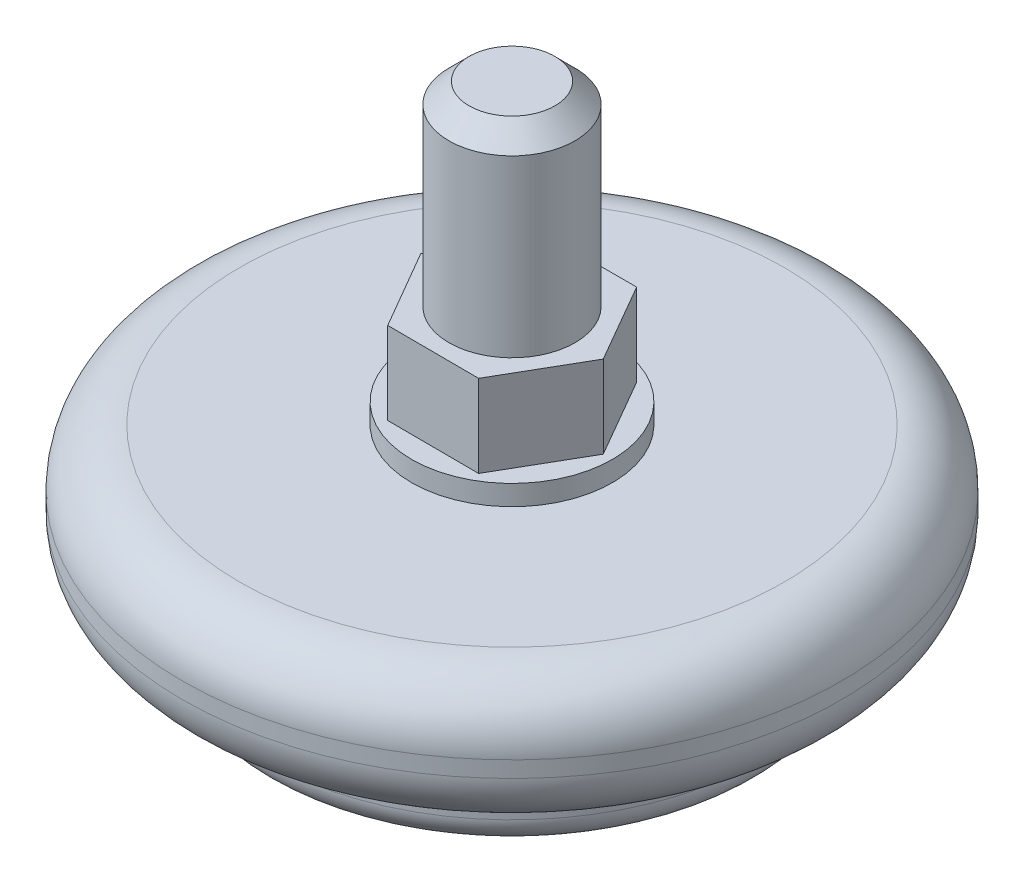
SolidWorks part; units mm, degrees
ref_plane "Front Plane" through (0, 0, 0) normal (0, 0, 1) x (1, 0, 0)
ref_plane "Top Plane" through (0, 0, 0) normal (0, 1, 0) x (1, 0, 0)
ref_plane "Right Plane" through (0, 0, 0) normal (1, 0, 0) x (0, 0, -1)
sketch "Sketch1" plane through (0, 0, 0) normal (0, 0, 1) x (1, 0, 0)
  line L0 (9.3737, -16.129) -> (26.107, -16.129)
  line L1 (5.533, -11.3792) -> (7.3417, -11.3792)
  line L2 (5.533, -1.524) -> (18.5253, -1.524)
  line L3 (1.215, -5.842) -> (1.215, -7.0612)
  line L4 (7.3417, -11.3792) -> (7.3417, -14.097)
  line L5 (26.107, 20.955) -> (22.8685, 20.955)
  line L6 (26.107, 20.955) -> (26.107, -16.129)
  line L17 (18.5253, 0) -> (19.2145, 0)
  line L18 (19.2145, 6.223) -> (21.3445, 6.223)
  line L19 (21.3445, 19.431) -> (21.3445, 6.223)
  line L20 (19.2145, 6.223) -> (19.2145, 0)
  line L21 (18.5253, 0) -> (18.5253, -1.524)
  line L23 (22.8685, 20.955) -> (21.3445, 19.431)
  arc A0 (1.215, -7.0612) -> (5.533, -11.3792) centre (5.533, -7.0612) ccw
  arc A1 (5.533, -1.524) -> (1.215, -5.842) centre (5.533, -5.842) ccw
  arc A2 (7.3417, -14.097) -> (9.3737, -16.129) centre (9.3737, -14.097) ccw
revolve "Revolve1" add sketch "Sketch1" angle 360 about L6
sketch "Sketch2" plane through (0, 6.223, 0) normal (0, 1, 0) x (1, 0, 0)
  line L1 (22.6607, 5.969) -> (29.5532, 5.969)
  line L2 (22.6607, 5.969) -> (29.5532, 5.969)
  line L3 (22.6607, -5.9384) -> (29.5532, -5.969)
  line L4 (29.5532, -5.969) -> (32.9994, 0)
  line L5 (22.6607, -5.9384) -> (19.2145, 0)
  line L6 (19.2145, 0) -> (22.6607, 5.969)
  line L7 (22.6607, 5.969) -> (29.5532, 5.969)
  line L8 (29.5532, 5.969) -> (32.9994, 0)
  circle A0 centre (26.107, 0) radius 6.8924 construction
  circle A1 centre (26.107, 0) radius 6.8924 construction
  circle M1 centre (26.107, 0) radius 6.8924
  circle M2 centre (26.107, 0) radius 4.7625
extrude "Cut-Extrude1" cut sketch "Sketch2" against normal up to surface (6.223 mm away) flip side to cut contours L8 L1 L6 L5 L3 L4 M1 M2
